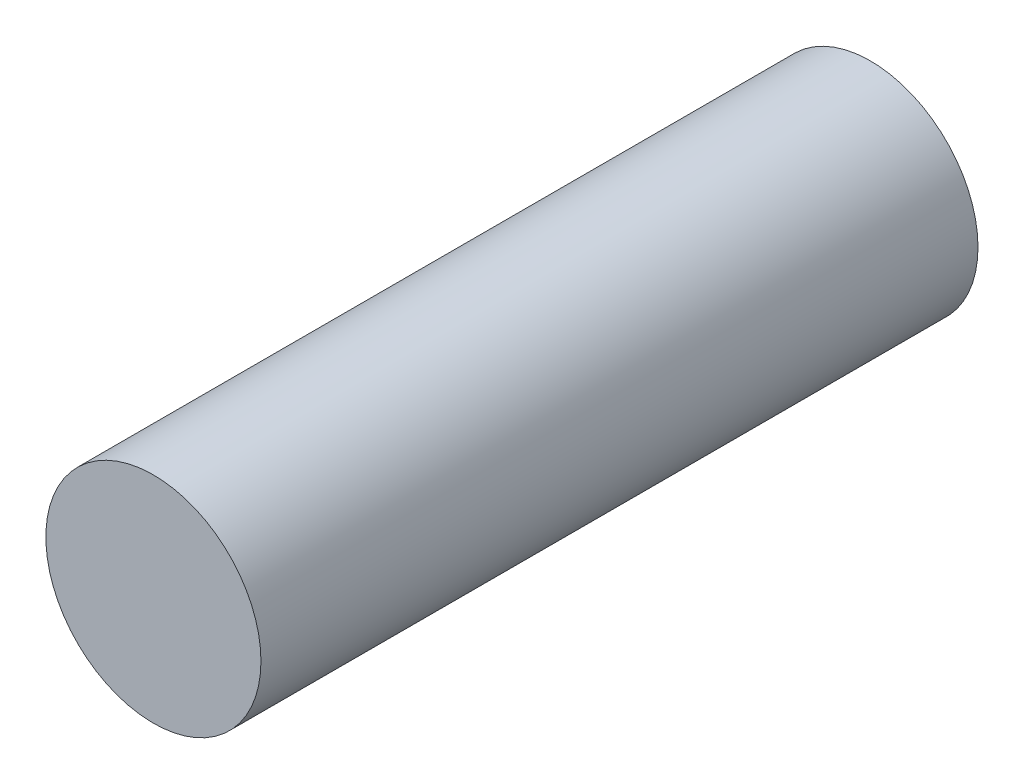
SolidWorks part; units mm, degrees
ref_plane "Plano frontal" through (0, 0, 0) normal (0, 0, 1) x (1, 0, 0)
ref_plane "Plano superior" through (0, 0, 0) normal (0, 1, 0) x (1, 0, 0)
ref_plane "Plano direito" through (0, 0, 0) normal (1, 0, 0) x (0, 0, -1)
sketch "Esboço1" plane through (0, 0, 0) normal (0, 0, 1) x (1, 0, 0)
  circle A0 centre (0, 0) radius 2.25
  dimension "D1" = 4.5
extrude "Ressalto-extrusão1" add sketch "Esboço1" along normal blind 15
